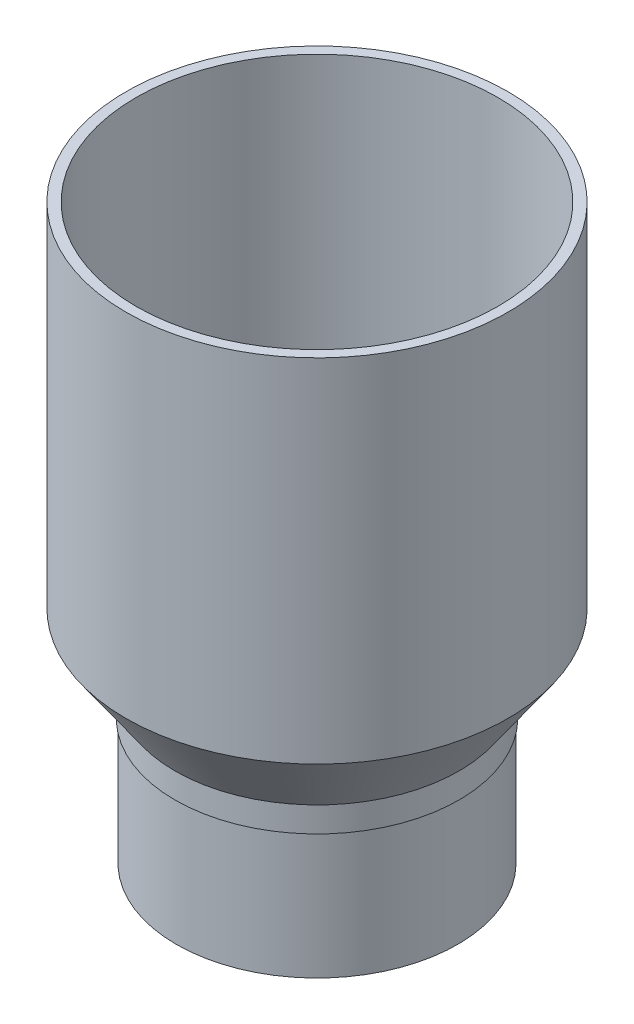
SolidWorks part; units mm, degrees
ref_plane "Front Plane" through (0, 0, 0) normal (0, 0, 1) x (1, 0, 0)
ref_plane "Top Plane" through (0, 0, 0) normal (0, 1, 0) x (1, 0, 0)
ref_plane "Right Plane" through (0, 0, 0) normal (1, 0, 0) x (0, 0, -1)
sketch "Sketch1" plane through (0, 0, 0) normal (0, 0, 1) x (1, 0, 0)
  line L0 (0, 88.7745) -> (0, -57.3806) construction
  line L1 (36, 75.1538) -> (36, 5.1538)
  line L2 (36, 5.1538) -> (26.2492, -8.7718)
  line L3 (26.2492, -8.7718) -> (26.2492, -13.7718)
  line L4 (26.2492, -13.7718) -> (26, -13.7718)
  line L5 (26, -13.7718) -> (26, -38.7718)
  line L6 (36, 75.1538) -> (38, 75.1538)
  line L7 (38, 75.1538) -> (38, 5.1538)
  line L8 (38, 5.1538) -> (28.2492, -8.7718)
  line L9 (28.2492, -8.7718) -> (28.2492, -13.7718)
  line L10 (28.2492, -13.7718) -> (28, -13.7718)
  line L11 (28, -13.7718) -> (28, -38.7718)
  line L12 (26, -38.7718) -> (28, -38.7718)
  point P5 (26, -26.2718)
  dimension "7" = 70
  dimension "D2" = 17
  dimension "D3" = 5
  dimension "D4" = 26
  dimension "D5" = 25
  dimension "D6" = 36
  dimension "D7" = 70
  dimension "D9" = 17
  dimension "D10" = 5
  dimension "D11" = 25
  dimension "D12" = 2
  dimension "D13" = 2
  dimension "D14" = 13.9256
revolve "Revolve1" add sketch "Sketch1" angle 360 about L0
